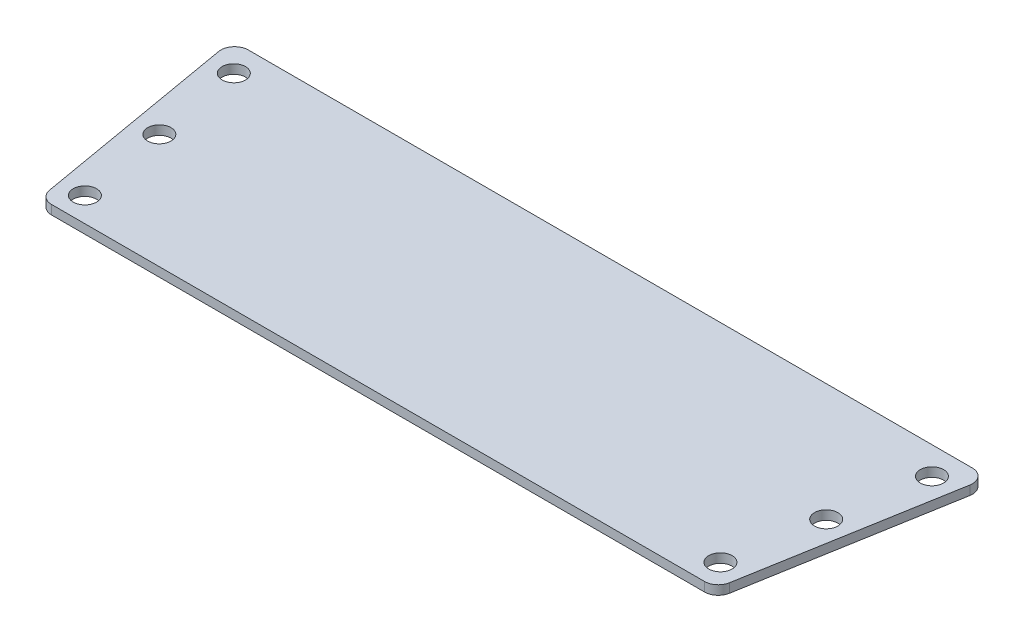
SolidWorks part; units mm, degrees
ref_plane "前视基准面" through (0, 0, 0) normal (0, 0, 1) x (1, 0, 0)
ref_plane "上视基准面" through (0, 0, 0) normal (0, 1, 0) x (1, 0, 0)
ref_plane "右视基准面" through (0, 0, 0) normal (1, 0, 0) x (0, 0, -1)
sketch "草图1" plane through (0, 0, 0) normal (0, 1, 0) x (1, 0, 0)
  line L14 (-100, 30) -> (100, 30)
  line L15 (-100, 30) -> (-100, -30)
  line L16 (-100, -30) -> (100, -30)
  line L17 (100, 30) -> (100, -30)
  line L18 (-100, 30) -> (100, -30) construction
  line L19 (-100, -30) -> (100, 30) construction
  point P0 (0, 0)
  dimension "D1" = 200
  dimension "D2" = 60
extrude "凸台-拉伸1" add sketch "草图1" along normal blind 2
sketch "草图3" plane through (0, 2, 0) normal (0, 1, 0) x (1, 0, 0)
  line L0 (-77.8265, -20.7713) -> (-86.6429, 30)
  line L2 (-77.8265, -20.7713) -> (82.1735, -20.7713)
  line L3 (82.1735, -20.7713) -> (90.9898, 30)
  line L4 (100, -30) -> (100, 30)
  line L5 (100, 30) -> (-100, 30)
  line L6 (-100, 30) -> (-100, -30)
  line L7 (-100, -30) -> (100, -30)
  line L8 (100, -30) -> (100, 30)
  line L9 (100, 30) -> (-100, 30)
  line L10 (-100, 30) -> (-100, -30)
  line L11 (-100, -30) -> (100, -30)
  circle A0 centre (-74.1534, 24) radius 2.55
  circle A1 centre (-70.7316, 4.2949) radius 2.55
  circle A2 centre (-67.3099, -15.4102) radius 2.55
  circle A3 centre (78.5003, 24) radius 2.55
  circle A4 centre (75.0785, 4.2949) radius 2.55
  circle A5 centre (71.6568, -15.4102) radius 2.55
  line M5 (100, -30) -> (100, 30)
  line M6 (100, 30) -> (-100, 30)
  line M7 (-100, 30) -> (-100, -30)
  line M8 (-100, -30) -> (100, -30)
  dimension "D2" = 5.1
  dimension "D1" = 0
extrude "切除-拉伸1" cut sketch "草图3" against normal through all contours L3 L2 L0 M6 M7 M8 M5 | A0 | A1 | A2 | A3 | A5 | A4
sketch "草图4" plane through (0, 0, 0) normal (0, -1, 0) x (1, 0, 0)
  line L0 (84.9, -30) -> (76.0837, 20.7713)
  line L1 (-80.5531, -30) -> (-71.7367, 20.7713)
  line L4 (90.9898, -30) -> (82.1735, 20.7713)
  line L5 (82.1735, 20.7713) -> (-77.8265, 20.7713)
  line L6 (-77.8265, 20.7713) -> (-86.6429, -30)
  line L7 (-86.6429, -30) -> (90.9898, -30)
  line L8 (90.9898, -30) -> (82.1735, 20.7713)
  line L9 (82.1735, 20.7713) -> (-77.8265, 20.7713)
  line L10 (-77.8265, 20.7713) -> (-86.6429, -30)
  line L11 (-86.6429, -30) -> (90.9898, -30)
  line M13 (90.9898, -30) -> (82.1735, 20.7713)
  line M14 (82.1735, 20.7713) -> (-77.8265, 20.7713)
  line M15 (-77.8265, 20.7713) -> (-86.6429, -30)
  line M16 (-86.6429, -30) -> (90.9898, -30)
  dimension "D2" = 6
  dimension "D3" = 6
  dimension "D1" = 0
extrude "切除-拉伸2" cut sketch "草图4" against normal through all contours L0 M16 M13 M14 | L1 M16 M14 M15
sketch "草图5" plane through (0, 0, 0) normal (0, -1, 0) x (1, 0, 0)
  line L0 (-6, -3) -> (-6, 0) construction
  line L1 (-6, 0) -> (0, 0) construction
  circle A0 centre (-6, -3) radius 17.5
  dimension "D1" = 35
  dimension "D2" = 3
  dimension "D3" = 6
extrude "切除-拉伸3" cut sketch "草图5" against normal blind 0.2
fillet "圆角1" radius 3 4 edges at (-80.5531, 1, -30) (-71.7367, 1, 20.7713) (76.0837, 1, 20.7713) (84.9, 1, -30)
